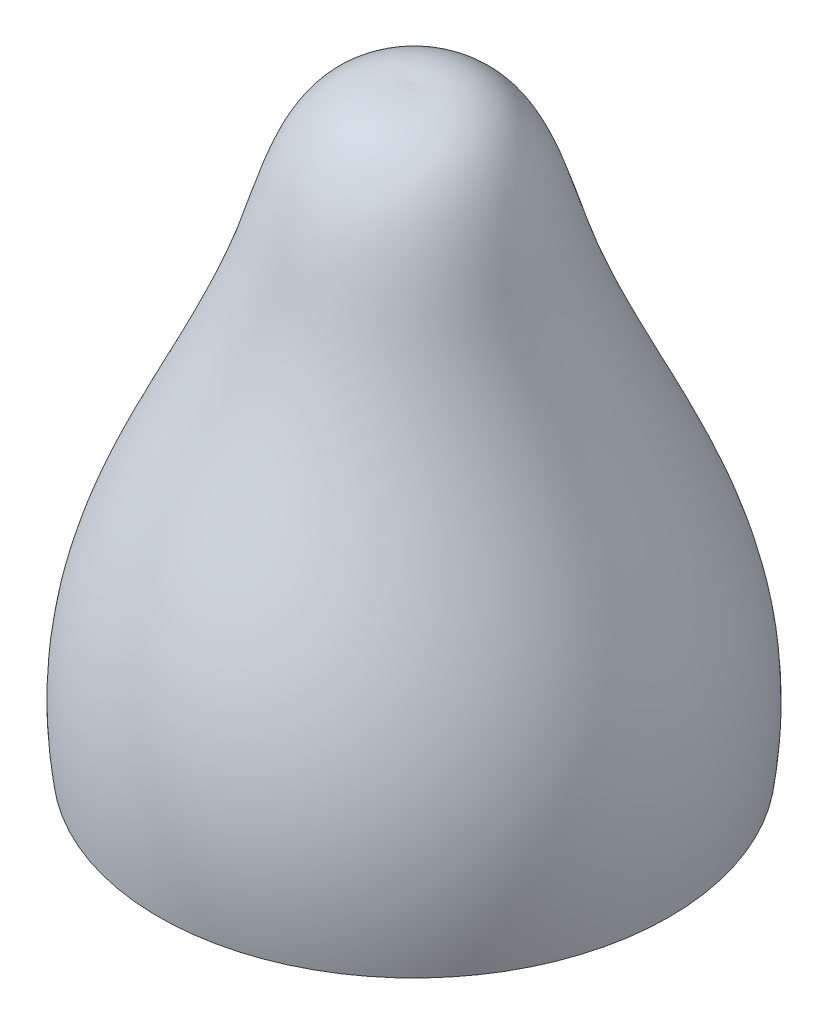
SolidWorks part; units mm, degrees
ref_plane "Front Plane" through (0, 0, 0) normal (0, 0, 1) x (1, 0, 0)
ref_plane "Top Plane" through (0, 0, 0) normal (0, 1, 0) x (1, 0, 0)
ref_plane "Right Plane" through (0, 0, 0) normal (1, 0, 0) x (0, 0, -1)
sketch "Sketch2" plane through (0, 0, 0) normal (0, 0, 1) x (1, 0, 0)
  line L0 (0, 0) -> (0, 7)
  line L1 (0, 0) -> (3, 0)
  spline S0 degree 3 poles (0, 7) (1.0682, 7.1115) (1.5785, 3.9644) (3.3133, 2.222) (3, 0) knots 0 0 0 0 0.308743 1 1 1 1
  dimension "D1" = 7
  dimension "D2" = 3
revolve "Revolve1" add sketch "Sketch2" angle 360 about L0
sketch "Sketch3" plane through (0, 0, 0) normal (0, -1, 0) x (1, 0, 0)
  circle A0 centre (0, 0) radius 1.5
extrude "Cut-Extrude1" cut sketch "Sketch3" against normal blind 4 contours A0
